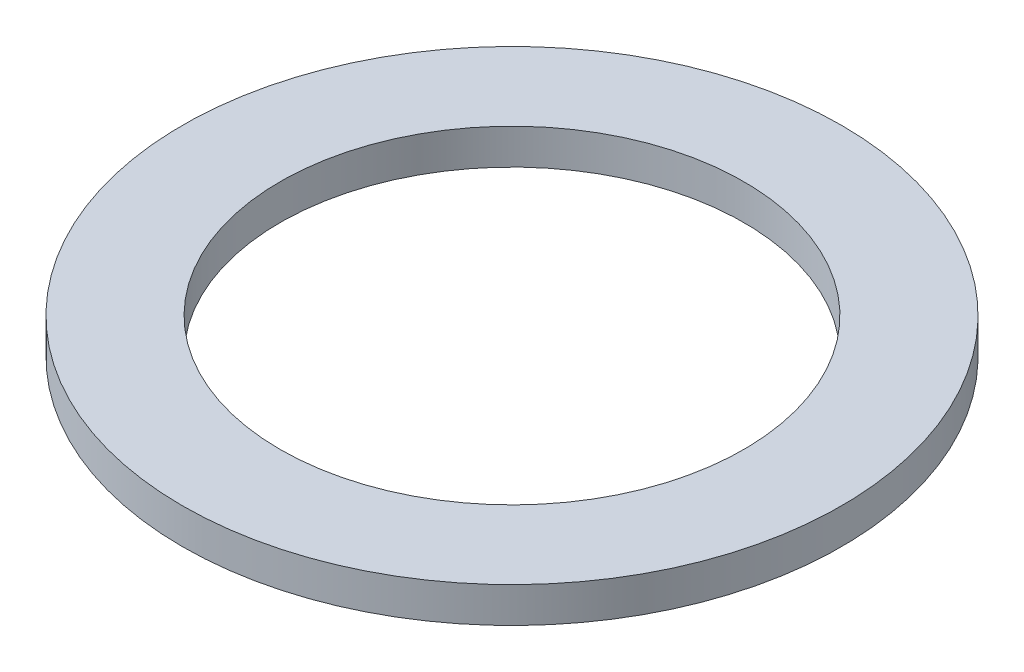
SolidWorks part; units mm, degrees
material "Copper"
ref_plane "Front Plane" through (0, 0, 0) normal (0, 0, 1) x (1, 0, 0)
ref_plane "Top Plane" through (0, 0, 0) normal (0, 1, 0) x (1, 0, 0)
ref_plane "Right Plane" through (0, 0, 0) normal (1, 0, 0) x (0, 0, -1)
sketch "Sketch1" plane through (0, 0, 0) normal (0, 1, 0) x (1, 0, 0)
  circle A0 centre (0, 0) radius 6.65
  circle A1 centre (0, 0) radius 9.45
  dimension "D1" = 2.8
  dimension "D2" = 13.3
extrude "Boss-Extrude2" add sketch "Sketch1" along normal blind 1.016
